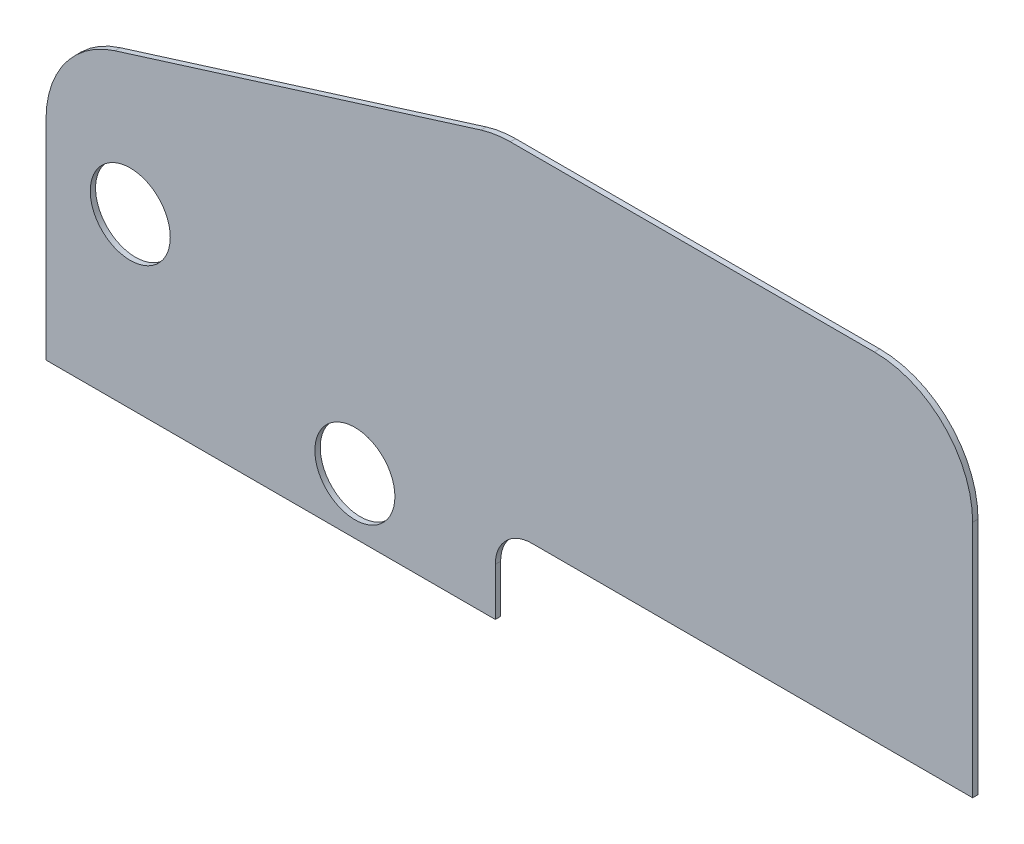
SolidWorks part; units mm, degrees
ref_plane "Plano frontal" through (0, 0, 0) normal (0, 0, 1) x (1, 0, 0)
ref_plane "Plano superior" through (0, 0, 0) normal (0, 1, 0) x (1, 0, 0)
ref_plane "Plano direito" through (0, 0, 0) normal (1, 0, 0) x (0, 0, -1)
sketch "Esboço1" plane through (0, 0, 0) normal (0, 0, 1) x (1, 0, 0)
  line L2 (-160, 70) -> (0, 120)
  line L3 (0, 120) -> (170, 120)
  line L4 (170, 120) -> (170, 0)
  line L5 (170, 0) -> (0, 0)
  line L6 (0, 0) -> (0, -30)
  line L7 (0, -30) -> (-160, -30)
  line L8 (-160, -30) -> (-160, 70)
  point P1 (0, 0)
  point P5 (-110, 72.9649)
  dimension "D1" = 100
  dimension "D2" = 170
  dimension "D3" = 120
  dimension "D4" = 160
  dimension "D5" = 30
extrude "Ressalto-extrusão1" add sketch "Esboço1" along normal blind 1.9
sketch "Esboço2" plane through (0, 0, 1.9) normal (0, 0, 1) x (1, 0, 0)
  line L2 (-160, -30) -> (0, -30) construction
  line L3 (-160, 70) -> (-160, -30) construction
  circle A0 centre (-50, -10) radius 14.25
  circle A1 centre (-130, 30) radius 14.25
  point P4 (-20.3176, -15.0143)
  point P5 (-79.8644, 12.9148)
  point P6 (-19.8723, -12.0079)
  point P7 (-80.0045, 23.2696)
  point P12 (-91.7821, -30)
  dimension "D1" = 28.5
  dimension "D2" = 30
  dimension "D3" = 60
  dimension "D4" = 110
  dimension "D5" = 20
extrude "Corte-extrusão1" cut sketch "Esboço2" against normal blind 1.9
fillet "Filete1" radius 13 1 edges at (0, 0, 0.95)
fillet "Filete2" radius 35 3 edges at (170, 120, 0.95) (0, 120, 0.95) (-160, 70, 0.95)
